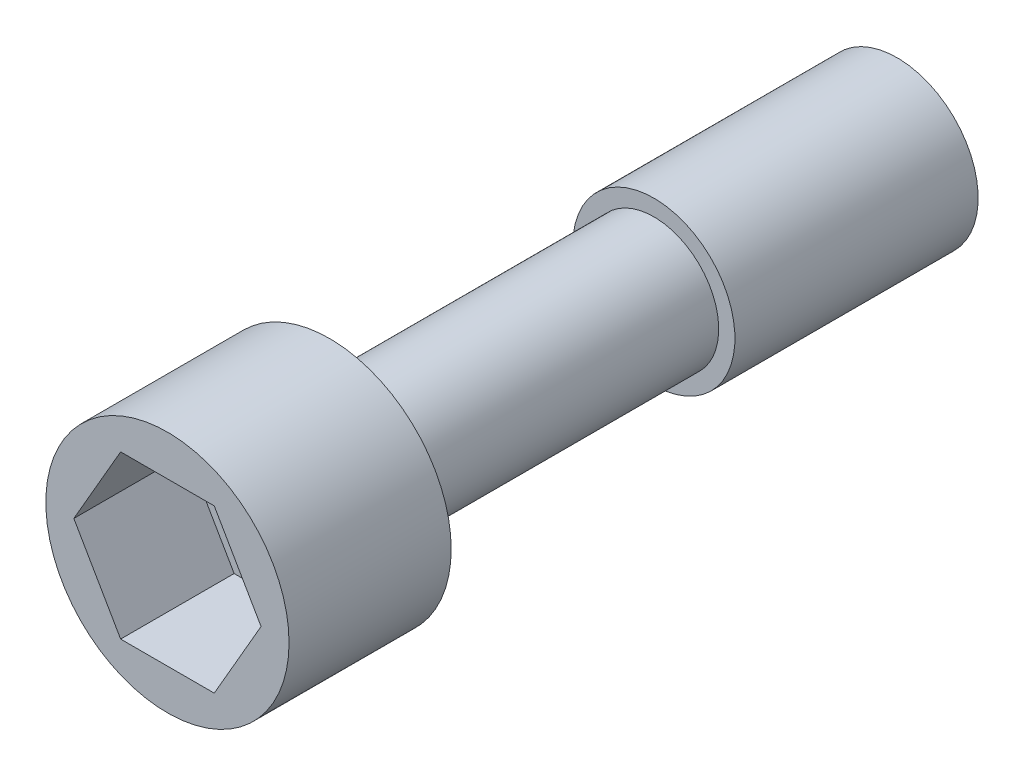
SolidWorks part; units mm, degrees
ref_plane "Front Plane" through (0, 0, 0) normal (0, 0, 1) x (1, 0, 0)
ref_plane "Top Plane" through (0, 0, 0) normal (0, 1, 0) x (1, 0, 0)
ref_plane "Right Plane" through (0, 0, 0) normal (1, 0, 0) x (0, 0, -1)
sketch "Sketch1" plane through (0, 0, 0) normal (0, 0, 1) x (1, 0, 0)
  circle A0 centre (0, 0) radius 7.5
  dimension "D1" = 15
extrude "Boss-Extrude1" add sketch "Sketch1" along normal blind 10
sketch "Sketch2" plane through (0, 0, 0) normal (0, 0, -1) x (-1, 0, 0)
  circle A0 centre (0, 0) radius 4
  dimension "D1" = 8
extrude "Boss-Extrude2" add sketch "Sketch2" along normal blind 20
sketch "Sketch3" plane through (0, 0, -20) normal (0, 0, -1) x (-1, 0, 0)
  circle A0 centre (0, 0) radius 5
  dimension "D1" = 10
extrude "Boss-Extrude3" add sketch "Sketch3" along normal blind 15
sketch "Sketch4" plane through (0, 0, 10) normal (0, 0, 1) x (1, 0, 0)
  line L1 (2.8868, 5) -> (-2.8868, 5)
  line L2 (-2.8868, 5) -> (-5.7735, 0)
  line L3 (-5.7735, 0) -> (-2.8868, -5)
  line L4 (-2.8868, -5) -> (2.8868, -5)
  line L5 (2.8868, -5) -> (5.7735, 0)
  line L6 (5.7735, 0) -> (2.8868, 5)
  circle A0 centre (0, 0) radius 5 construction
  dimension "D1" = 10
extrude "Cut-Extrude1" cut sketch "Sketch4" against normal blind 7
